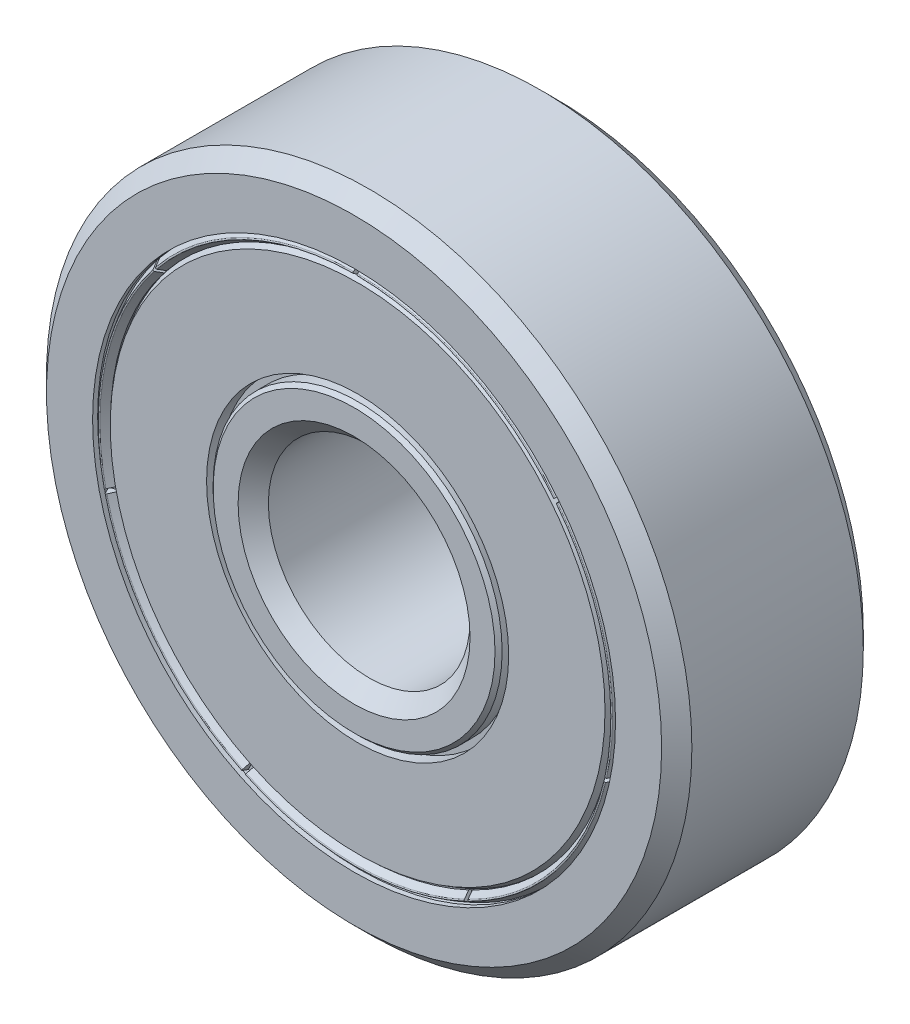
SolidWorks part; units mm, degrees
material "AISI 1045 钢，冷拔"
ref_plane "Front Plane" through (0, 0, 0) normal (0, 0, 1) x (1, 0, 0)
ref_plane "Top Plane" through (0, 0, 0) normal (0, 1, 0) x (1, 0, 0)
ref_plane "Right Plane" through (0, 0, 0) normal (1, 0, 0) x (0, 0, -1)
sketch "Sketch1" plane through (0, 0, 0) normal (0, 0, 1) x (1, 0, 0)
  circle A0 centre (0, 0) radius 2.5
  circle A1 centre (0, 0) radius 8
  dimension "OD" = 16
  dimension "ID" = 5
sketch "Sketch2" plane through (0, 0, 0) normal (1, 0, 0) x (0, 0, -1)
  line L0 (-2.5, 8) -> (2.5, 8)
  line L1 (-2.5, 2.5) -> (-2.5, -2.5) construction
  line L2 (2.5, 8) -> (2.5, -8) construction
  line L3 (-2.5, 0) -> (2.5, 0) construction
  line L6 (0, 8) -> (0, 2.5) construction
  circle A0 centre (0, 5.25) radius 1.925 construction
  point P8 (0, 8)
  dimension "Approx. Ball Dia." = 3.85
  dimension "Width" = 5
  dimension "For Shaft Diameter" = 5
  dimension "For Housing ID" = 16
sketch "Sketch3" plane through (0, 0, 0) normal (1, 0, 0) x (0, 0, -1)
  line L0 (0, 0) -> (0, 5) construction
  line L1 (-2.5, 2.5) -> (-2.5, -2.5) construction
  line L2 (2.125, 8) -> (-2.125, 8)
  line L3 (-2.125, 8) -> (-2.5, 7.625)
  line L4 (-2.5, 7.625) -> (-2.5, 6.4824)
  line L5 (-2.5, 6.4824) -> (-2.375, 6.4824)
  line L6 (-2.375, 6.4824) -> (-2.375, 6.8287)
  line L7 (-2.375, 6.8287) -> (-2.2866, 6.9171)
  line L8 (-2.2866, 6.9171) -> (-0.9625, 6.9171)
  line L10 (-2.5, 8) -> (2.5, 8) construction
  line L12 (-2.375, 6.8287) -> (-2.375, 7.175) construction
  line L13 (2.2866, 6.9171) -> (0.9625, 6.9171)
  line L14 (2.375, 6.8287) -> (2.2866, 6.9171)
  line L15 (2.375, 6.4824) -> (2.375, 6.8287)
  line L16 (2.5, 6.4824) -> (2.375, 6.4824)
  line L17 (2.5, 7.625) -> (2.5, 6.4824)
  line L18 (2.125, 8) -> (2.5, 7.625)
  line L19 (2.125, 2.5) -> (-2.125, 2.5)
  line L20 (-2.125, 2.5) -> (-2.5, 2.875)
  line L21 (-2.5, 2.875) -> (-2.5, 3.4945)
  line L22 (-2.5, 3.4945) -> (-2.4116, 3.5829)
  line L23 (-2.4116, 3.5829) -> (-0.9625, 3.5829)
  line L25 (2.4116, 3.5829) -> (0.9625, 3.5829)
  line L26 (2.5, 3.4945) -> (2.4116, 3.5829)
  line L27 (2.5, 2.875) -> (2.5, 3.4945)
  line L28 (2.125, 2.5) -> (2.5, 2.875)
  circle A2 centre (0, 5.25) radius 1.925 construction
  arc A3 (-0.9625, 6.9171) -> (0.9625, 6.9171) centre (0, 5.25) cw
  arc A4 (-0.9625, 3.5829) -> (0.9625, 3.5829) centre (0, 5.25) ccw
  point P5 (0, 7.175)
  point P31 (0, 8)
  point P37 (0, 2.5)
  dimension "D1" = 45
  dimension "D2" = 0.125
  dimension "D3" = 1.925
  dimension "D4" = 0.375
revolve "Revolve1" add sketch "Sketch3" angle 360 about L3
sketch "Sketch4" plane through (0, 0, 0) normal (1, 0, 0) x (0, 0, -1)
  line L0 (0, 7.175) -> (0, 3.325)
  line L1 (0, 8) -> (0, 2.5) construction
  circle A0 centre (0, 5.25) radius 1.925 construction
  arc A1 (0, 3.325) -> (0, 7.175) centre (0, 5.25) cw
revolve "Revolve2" add sketch "Sketch4" angle 360 about L6
pattern_circular "CirPattern1" count 7 over 360 about axis through (0, 0, 0) along (0, 0, 1) of bodies 106
sketch "Sketch5" plane through (0, 0, 0) normal (1, 0, 0) x (0, 0, -1)
  line L0 (-1.925, 5.25) -> (-1.925, 3.5829) construction
  line L1 (-2.4116, 3.5829) -> (-0.9625, 3.5829) construction
  line L3 (-1.925, 3.5829) -> (-2.0872, 3.5829)
  line L4 (-2.0872, 3.5829) -> (-2.0872, 3.7451)
  line L5 (-2.0872, 3.7451) -> (-2.4116, 3.7451)
  line L6 (-2.4116, 3.7451) -> (-2.4116, 6.1329)
  line L7 (-2.4116, 6.1329) -> (-2.0872, 6.3202)
  line L8 (-2.0872, 6.3202) -> (-1.925, 6.3202)
  line L9 (-1.925, 6.3202) -> (-1.925, 3.5829)
  line L10 (0, 5.25) -> (0, 8) construction
  line L11 (2.0872, 6.3202) -> (1.925, 6.3202)
  line L12 (2.4116, 6.1329) -> (2.0872, 6.3202)
  line L13 (2.4116, 3.7451) -> (2.4116, 6.1329)
  line L14 (2.0872, 3.7451) -> (2.4116, 3.7451)
  line L15 (2.0872, 3.5829) -> (2.0872, 3.7451)
  line L16 (1.925, 3.5829) -> (2.0872, 3.5829)
  line L17 (1.925, 6.3202) -> (1.925, 3.5829)
  line L18 (-2.4116, 6.1329) -> (-2.2494, 6.1329) construction
  line L19 (-2.2494, 6.1329) -> (-2.0872, 6.1329) construction
  line L20 (-2.0872, 6.1329) -> (-1.925, 6.1329) construction
  line L21 (-2.0872, 6.3202) -> (-2.0872, 6.4824) construction
  circle A0 centre (0, 5.25) radius 1.925 construction
  dimension "D1" = 30
revolve "Revolve3" add sketch "Sketch5" angle 360 about L3
sketch "Sketch6" plane through (0, 0, 0) normal (1, 0, 0) x (0, 0, -1)
  line L0 (-2.2373, 6.4824) -> (-2.2812, 6.4824)
  line L1 (-2.2812, 6.4824) -> (-2.5, 6.3561)
  line L2 (-2.5, 6.3561) -> (-2.3123, 6.2247)
  line L4 (-2.4116, 6.1329) -> (-2.0872, 6.3202) construction
  line L5 (-2.2373, 6.2335) -> (-2.2373, 6.4824)
  line L6 (-2.5, 6.4824) -> (-2.375, 6.4824) construction
  line L7 (-2.3123, 6.2247) -> (-2.2873, 6.2247)
  line L8 (-2.2873, 6.2247) -> (-2.2373, 6.2335)
  line L9 (-2.5, 7.625) -> (-2.5, -7.625) construction
  line L11 (-2.2873, 6.2247) -> (-2.2623, 6.2247) construction
  line L12 (-2.2623, 6.2247) -> (-2.2373, 6.2247) construction
  point P27 (-2.2593, 6.4824)
  dimension "D1" = 30
  dimension "D3" = 10
  dimension "D2" = 35
  dimension "D4" = 0.025
  dimension "D5" = 0.2188
revolve "Revolve4" add sketch "Sketch6" angle 360 about L3
fillet "Fillet1" radius 0.025 1 edges at (6.3561, 0, 2.5)
sketch "Sketch7" plane through (0, 0, 0) normal (0, 0, 1) x (1, 0, 0)
  line L0 (-0.05, 6.4824) -> (-0.05, 6.5824)
  line L1 (-0.05, 6.4824) -> (0.05, 6.4824) construction
  line L2 (-0.05, 6.4824) -> (-0.05, 6.2247)
  line L3 (-0.05, 6.2247) -> (0.05, 6.2247) construction
  line L4 (0.05, 6.4824) -> (0.05, 6.2247)
  line L5 (-0.05, 6.5824) -> (0.05, 6.5824)
  line L6 (0.05, 6.5824) -> (0.05, 6.4824)
  line L7 (-0.05, 6.2247) -> (-0.05, 6.1247)
  line L8 (-0.05, 6.1247) -> (0.05, 6.1247)
  line L9 (0.05, 6.1247) -> (0.05, 6.2247)
  dimension "D1" = 0.1
extrude "Cut-Extrude1" cut sketch "Sketch7" along normal through all from vertex at 2.2593 starting at point (0, 6.4824, 2.2593)
pattern_circular "CirPattern2" count 7 over 360 about axis through (0, 0, 0) along (0, 0, 1) of "Cut-Extrude1"
mirror "Mirror1" about plane through (0, 0, 0) normal (0, 0, 1) of bodies 120
equation "\"Approx. Ball Dia.@Sketch2\"=( \"OD@Sketch1\" - \"ID@Sketch1\" )  * .5 * .7"
equation "\"D2@Sketch3\"=\"Width@Sketch2\"*.025"
equation "\"D3@Sketch3\"=\"Approx. Ball Dia.@Sketch2\"*.5"
equation "\"D4@Sketch3\"=\"Width@Sketch2\"*.075"
equation "\"Approx No of Balls\"= ( pi * \"OD@Sketch1\" ) * .5 / \"Approx. Ball Dia.@Sketch2\""
equation "\"D1@CirPattern1\"=\"Approx No of Balls\""
equation "\"D4@Sketch6\"=\"D2@Sketch3\"*.2"
equation "\"D1@CirPattern2\"=\"Approx No of Balls\""
equation "\"D5@Sketch6\"=\"D2@Sketch3\"*1.75"
equation "\"D1@Fillet1\"=\"d4@sketch6\""
